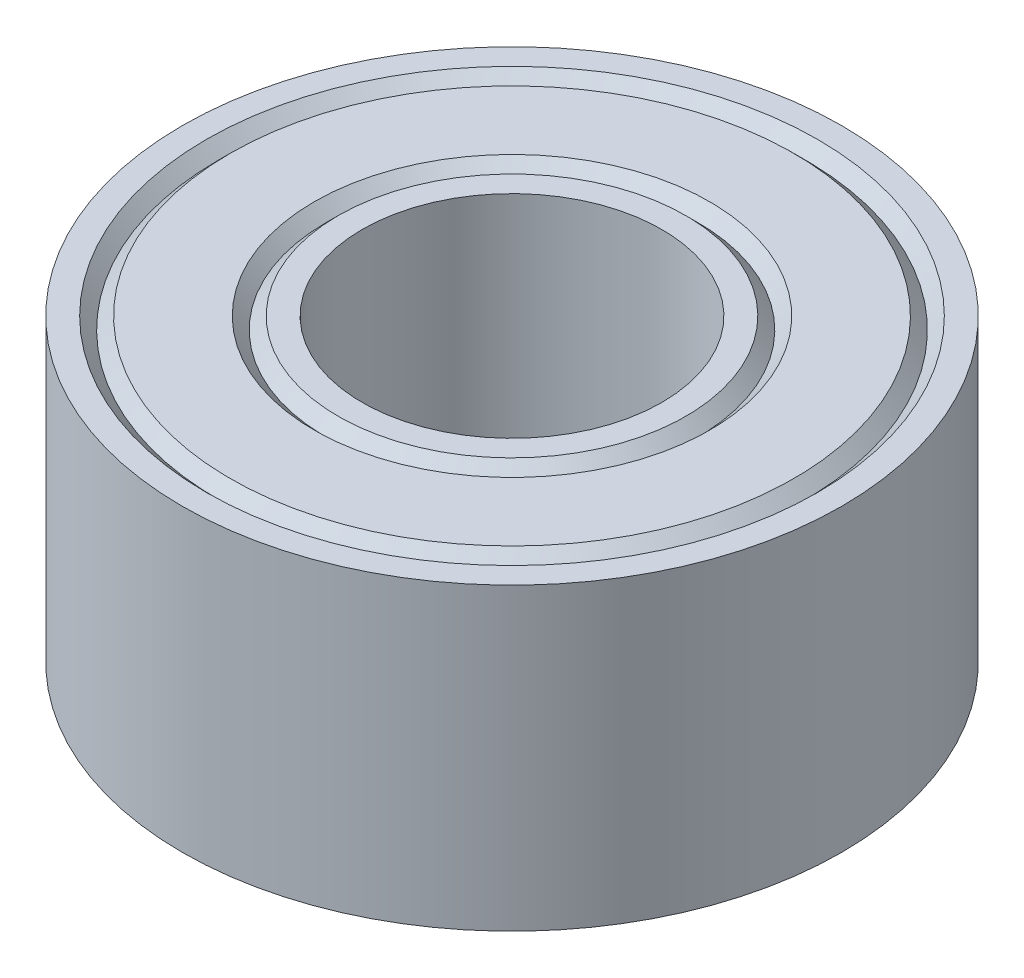
SolidWorks part; units mm, degrees
ref_plane "Front Plane" through (0, 0, 0) normal (0, 0, 1) x (1, 0, 0)
ref_plane "Top Plane" through (0, 0, 0) normal (0, 1, 0) x (1, 0, 0)
ref_plane "Right Plane" through (0, 0, 0) normal (1, 0, 0) x (0, 0, -1)
sketch "Sketch1" plane through (0, 0, 0) normal (0, 0, 1) x (1, 0, 0)
  line L0 (0, 2.5) -> (0, -2.5) construction
  line L1 (-2.5, 2.5) -> (-2.9, 2.5)
  line L2 (-2.5, 2.5) -> (-2.5, -2.5)
  line L3 (-2.5, -2.5) -> (-2.9, -2.5)
  line L4 (-5.5, 2.5) -> (-5.5, -2.5)
  line L5 (-5.1, 2.5) -> (-4.9, 2.3)
  line L6 (-4.9, 2.3) -> (-4.7, 2.5)
  line L7 (-3.3, 2.5) -> (-3.1, 2.3)
  line L8 (-3.1, 2.3) -> (-2.9, 2.5)
  line L9 (-5.1, -2.5) -> (-4.9, -2.3)
  line L10 (-4.9, -2.3) -> (-4.7, -2.5)
  line L11 (-3.3, -2.5) -> (-3.1, -2.3)
  line L12 (-3.1, -2.3) -> (-2.9, -2.5)
  line L13 (-3.3, -2.5) -> (-4.7, -2.5)
  line L14 (-5.1, -2.5) -> (-5.5, -2.5)
  line L15 (-5.1, 2.5) -> (-5.5, 2.5)
  line L16 (-3.3, 2.5) -> (-4.7, 2.5)
  line L17 (-4.9, 2.3) -> (-3.1, 2.3) construction
  line L18 (-4.9, 2.3) -> (-4.9, -2.3) construction
  line L19 (-3.1, -2.3) -> (-4.9, -2.3) construction
  line L20 (-3.1, 2.3) -> (-3.1, -2.3) construction
  line L21 (-4.9, 0) -> (-4.3, 0) construction
  line L22 (-2.9, 2.5) -> (-3.3, 2.5) construction
  line L23 (-4.3, 0) -> (-3.7, 0) construction
  line L24 (-4.9, 0) -> (-5.5, 0) construction
  line L25 (-3.7, 0) -> (-3.1, 0) construction
  line L26 (-3.1, 0) -> (-2.5, 0) construction
  dimension "D1" = 5
  dimension "D2" = 5
  dimension "D3" = 11
revolve "Revolve1" add sketch "Sketch1" angle 360 about L0
